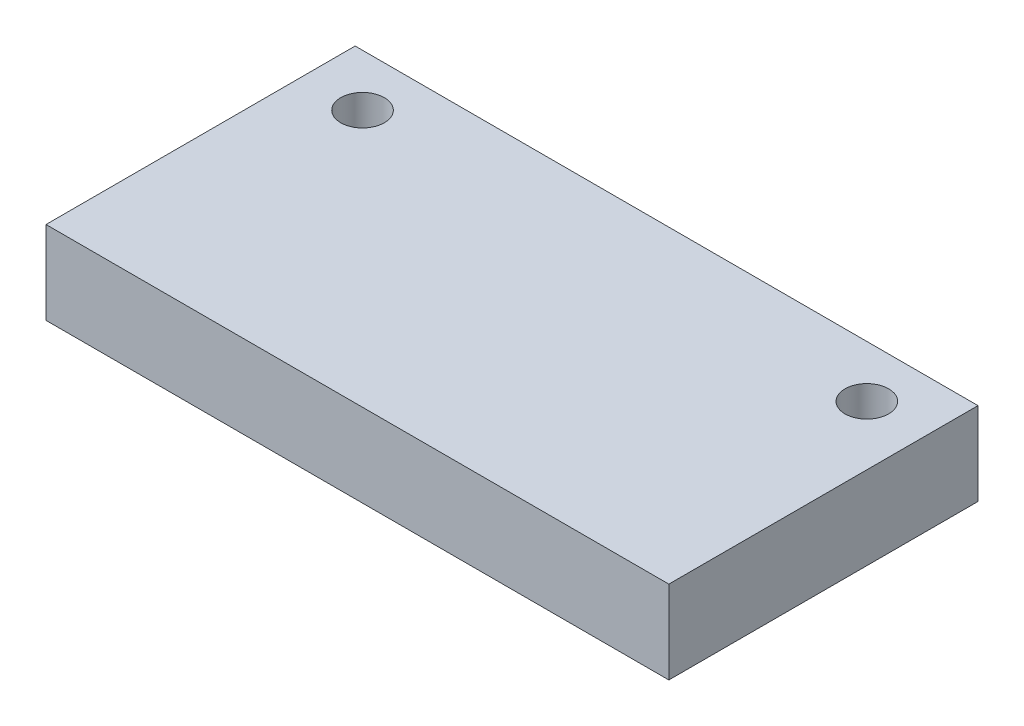
SolidWorks part; units mm, degrees
ref_plane "Front Plane" through (0, 0, 0) normal (0, 0, 1) x (1, 0, 0)
ref_plane "Top Plane" through (0, 0, 0) normal (0, 1, 0) x (1, 0, 0)
ref_plane "Right Plane" through (0, 0, 0) normal (1, 0, 0) x (0, 0, -1)
sketch "Sketch1" plane through (0, 0, 0) normal (0, 1, 0) x (1, 0, 0)
  line L0 (-12.1449, 0) -> (12.1449, 0) construction
  line L1 (-15, -2.5) -> (15, -2.5)
  line L2 (-15, -2.5) -> (-15, 2.5)
  line L3 (-15, 2.5) -> (15, 2.5)
  line L4 (15, -2.5) -> (15, 2.5)
  line L5 (0, 2.5) -> (0, 0) construction
  line L6 (0, 0) -> (0, -2.5) construction
  line L9 (-15, -2.5) -> (15, -2.5)
  line L10 (-15, -2.5) -> (-15, -12.391)
  line L11 (-15, -12.391) -> (15, -12.391)
  line L12 (15, -2.5) -> (15, -12.391)
  circle A0 centre (-12.1449, 0) radius 1.05
  circle A1 centre (12.1449, 0) radius 1.05
  point P0 (0, 0)
  dimension "D3" = 2.1
  dimension "D1" = 30
  dimension "D2" = 5
  dimension "D4" = 24.2899
extrude "Boss-Extrude1" add sketch "Sketch1" along normal blind 4 contours L1 L4 L3 L2 A1 A0 | L12 L1 L10 L11
